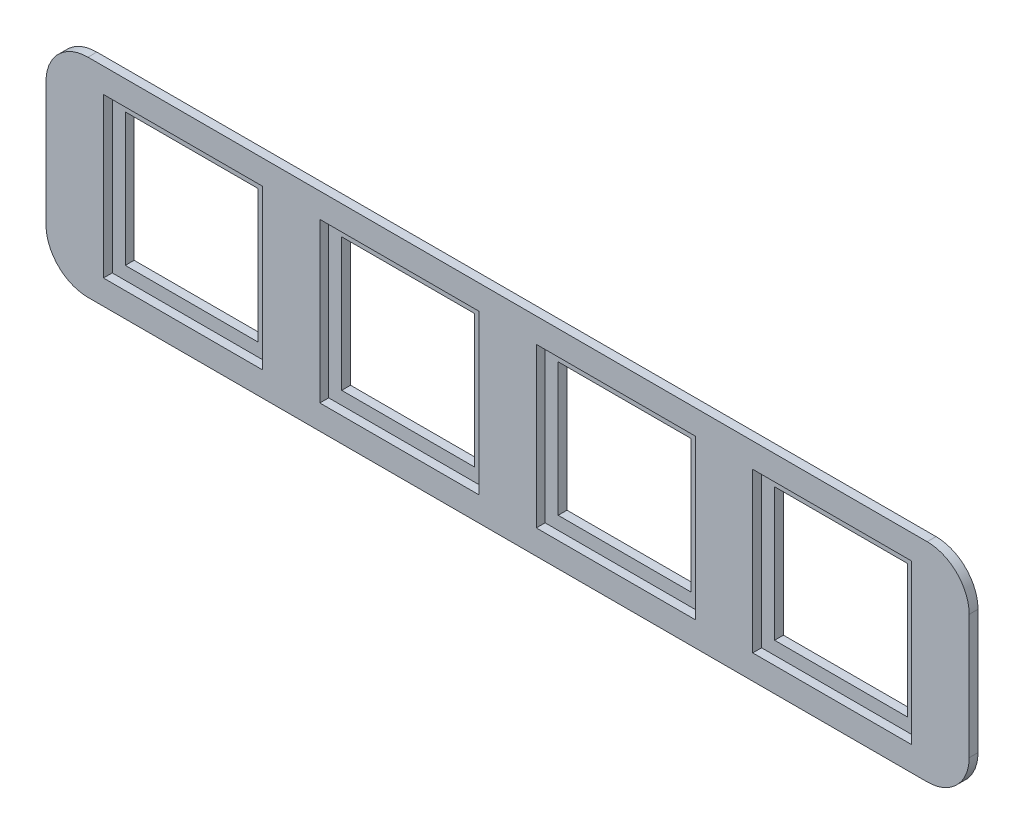
SolidWorks part; units mm, degrees
ref_plane "Plan de face" through (0, 0, 0) normal (0, 0, 1) x (1, 0, 0)
ref_plane "Plan de dessus" through (0, 0, 0) normal (0, 1, 0) x (1, 0, 0)
ref_plane "Plan de droite" through (0, 0, 0) normal (1, 0, 0) x (0, 0, -1)
sketch "Esquisse1" plane through (0, 0, 0) normal (0, 0, 1) x (1, 0, 0)
  line L1 (-95, -23.55) -> (95, -23.55)
  line L2 (-104.5, -14.05) -> (-104.5, 14.05)
  line L3 (-95, 23.55) -> (95, 23.55)
  line L4 (104.5, -14.05) -> (104.5, 14.05)
  line L5 (-104.5, -23.55) -> (104.5, 23.55) construction
  line L6 (-104.5, 23.55) -> (104.5, -23.55) construction
  arc A0 (95, 23.55) -> (104.5, 14.05) centre (95, 14.05) cw
  arc A1 (95, -23.55) -> (104.5, -14.05) centre (95, -14.05) ccw
  arc A2 (-95, -23.55) -> (-104.5, -14.05) centre (-95, -14.05) cw
  arc A3 (-104.5, 14.05) -> (-95, 23.55) centre (-95, 14.05) cw
  point P0 (0, 0)
  dimension "D3" = 9.5
  dimension "D1" = 47.1
  dimension "D2" = 209
extrude "Boss.-Extru.1" add sketch "Esquisse1" along normal blind 2
sketch "Esquisse6" plane through (0, 0, 0) normal (0, 0, -1) x (-1, 0, 0)
  line L1 (-95, -19.05) -> (95, -19.05)
  line L2 (-100, -14.05) -> (-100, 14.05)
  line L3 (-95, 19.05) -> (95, 19.05)
  line L4 (100, -14.05) -> (100, 14.05)
  line L5 (-100, -19.05) -> (100, 19.05) construction
  line L6 (-100, 19.05) -> (100, -19.05) construction
  arc A0 (95, 19.05) -> (100, 14.05) centre (95, 14.05) cw
  arc A1 (95, -19.05) -> (100, -14.05) centre (95, -14.05) ccw
  arc A2 (-95, -19.05) -> (-100, -14.05) centre (-95, -14.05) cw
  arc A3 (-100, 14.05) -> (-95, 19.05) centre (-95, 14.05) cw
  point P0 (0, 0)
  dimension "D3" = 5
  dimension "D1" = 38.1
  dimension "D2" = 200
extrude "Boss.-Extru.3" add sketch "Esquisse6" along normal blind 2
sketch "Esquisse7" plane through (0, 0, 2) normal (0, 0, 1) x (1, 0, 0)
  line L0 (-104.5, 14.05) -> (-104.5, -14.05) construction
  line L5 (-91.5, -18) -> (-55.5, -18)
  line L6 (-91.5, -18) -> (-91.5, 18)
  line L7 (-91.5, 18) -> (-55.5, 18)
  line L8 (-55.5, -18) -> (-55.5, 18)
  line L9 (-91.5, -18) -> (-55.5, 18) construction
  line L10 (-91.5, 18) -> (-55.5, -18) construction
  line L11 (95, 23.55) -> (-95, 23.55) construction
  line L12 (-42.5, -18) -> (-6.5, -18)
  line L13 (-42.5, -18) -> (-42.5, 18)
  line L14 (-42.5, 18) -> (-6.5, 18)
  line L15 (-6.5, -18) -> (-6.5, 18)
  line L16 (-42.5, -18) -> (-6.5, 18) construction
  line L17 (-42.5, 18) -> (-6.5, -18) construction
  line L18 (6.5, -18) -> (42.5, -18)
  line L19 (6.5, -18) -> (6.5, 18)
  line L20 (6.5, 18) -> (42.5, 18)
  line L21 (42.5, -18) -> (42.5, 18)
  line L22 (6.5, -18) -> (42.5, 18) construction
  line L23 (6.5, 18) -> (42.5, -18) construction
  line L24 (55.5, -18) -> (91.5, -18)
  line L25 (55.5, -18) -> (55.5, 18)
  line L26 (55.5, 18) -> (91.5, 18)
  line L27 (91.5, -18) -> (91.5, 18)
  line L28 (55.5, -18) -> (91.5, 18) construction
  line L29 (55.5, 18) -> (91.5, -18) construction
  point P0 (0, 0)
  point P1 (-73.5, 0)
  point P9 (-24.5, 0)
  point P14 (24.5, 0)
  point P19 (73.5, 0)
  dimension "D1" = 13
  dimension "D2" = 36
  dimension "D3" = 36
  dimension "D4" = 13
  dimension "D5" = 13
  dimension "D6" = 36
  dimension "D7" = 36
  dimension "D8" = 13
  dimension "D9" = 36
  dimension "D10" = 36
  dimension "D11" = 36
  dimension "D12" = 36
  dimension "D13" = 5.55
extrude "Enlèv. mat.-Extru.4" cut sketch "Esquisse7" against normal blind 2
sketch "Esquisse8" plane through (0, 0, -2) normal (0, 0, -1) x (-1, 0, 0)
  line L0 (-104.5, -14.05) -> (-104.5, 14.05) construction
  line L5 (-88.55, -15.05) -> (-58.45, -15.05)
  line L6 (-88.55, -15.05) -> (-88.55, 15.05)
  line L7 (-88.55, 15.05) -> (-58.45, 15.05)
  line L8 (-58.45, -15.05) -> (-58.45, 15.05)
  line L9 (-88.55, -15.05) -> (-58.45, 15.05) construction
  line L10 (-88.55, 15.05) -> (-58.45, -15.05) construction
  line L11 (-95, 23.55) -> (95, 23.55) construction
  line L13 (-39.55, -15.05) -> (-9.45, -15.05)
  line L14 (-39.55, -15.05) -> (-39.55, 15.05)
  line L15 (-39.55, 15.05) -> (-9.45, 15.05)
  line L16 (-9.45, -15.05) -> (-9.45, 15.05)
  line L17 (-39.55, -15.05) -> (-9.45, 15.05) construction
  line L18 (-39.55, 15.05) -> (-9.45, -15.05) construction
  line L19 (9.45, -15.05) -> (39.55, -15.05)
  line L20 (9.45, -15.05) -> (9.45, 15.05)
  line L21 (9.45, 15.05) -> (39.55, 15.05)
  line L22 (39.55, -15.05) -> (39.55, 15.05)
  line L23 (9.45, -15.05) -> (39.55, 15.05) construction
  line L24 (9.45, 15.05) -> (39.55, -15.05) construction
  line L25 (58.45, -15.05) -> (88.55, -15.05)
  line L26 (58.45, -15.05) -> (58.45, 15.05)
  line L27 (58.45, 15.05) -> (88.55, 15.05)
  line L28 (88.55, -15.05) -> (88.55, 15.05)
  line L29 (58.45, -15.05) -> (88.55, 15.05) construction
  line L30 (58.45, 15.05) -> (88.55, -15.05) construction
  point P0 (0, 0)
  point P1 (-73.5, 0)
  point P11 (-24.5, 0)
  point P16 (24.5, 0)
  point P21 (73.5, 0)
  dimension "D1" = 15.95
  dimension "D2" = 30.1
  dimension "D3" = 30.1
  dimension "D4" = 8.5
  dimension "D5" = 30.1
  dimension "D6" = 30.1
  dimension "D7" = 18.9
  dimension "D8" = 18.9
  dimension "D9" = 30.1
  dimension "D10" = 30.1
  dimension "D11" = 18.9
  dimension "D12" = 30.1
  dimension "D13" = 30.1
extrude "Enlèv. mat.-Extru.5" cut sketch "Esquisse8" against normal through all
